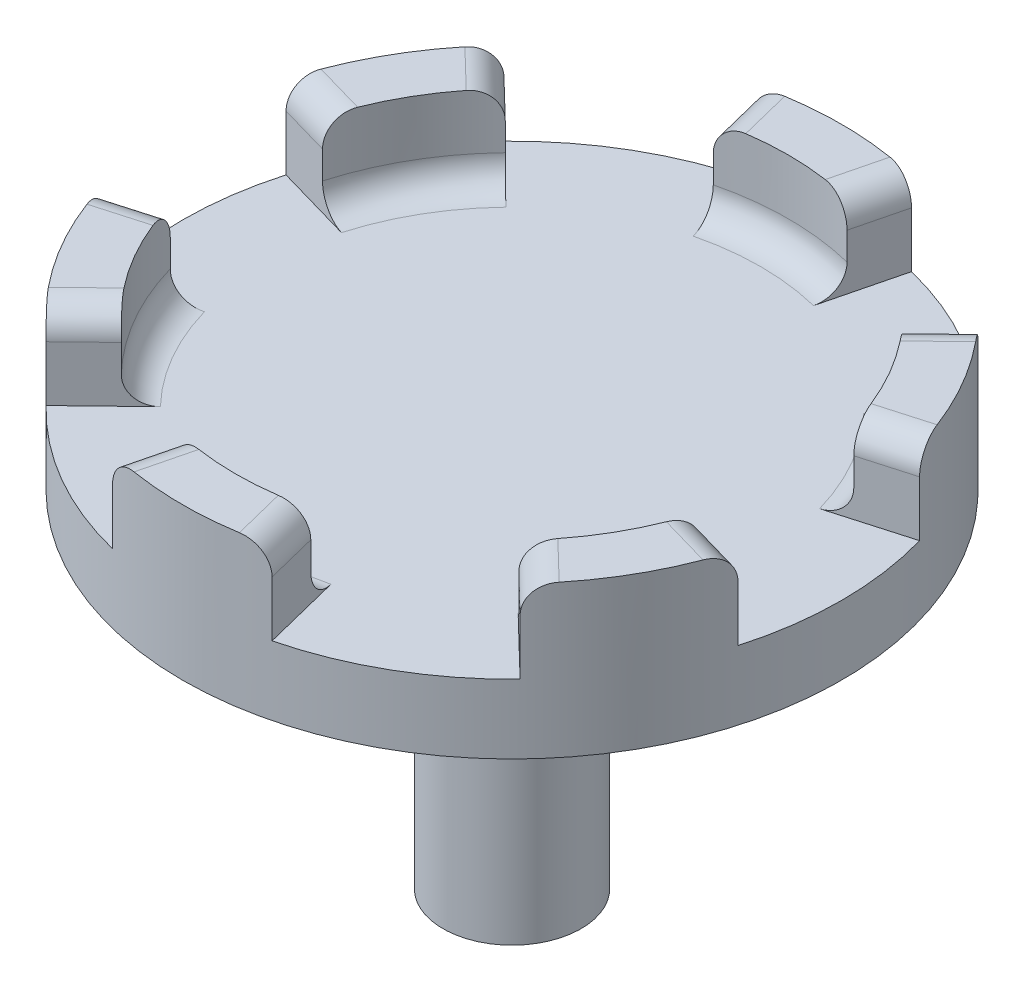
SolidWorks part; units mm, degrees
ref_plane "Front Plane" through (0, 0, 0) normal (0, 0, 1) x (1, 0, 0)
ref_plane "Top Plane" through (0, 0, 0) normal (0, 1, 0) x (1, 0, 0)
ref_plane "Right Plane" through (0, 0, 0) normal (1, 0, 0) x (0, 0, -1)
sketch "Sketch1" plane through (0, 0, 0) normal (0, 1, 0) x (1, 0, 0)
  circle A0 centre (0, 0) radius 30.2895
  dimension "D1" = 60.579
extrude "Boss-Extrude1" add sketch "Sketch1" along normal blind 6.35
sketch "Sketch2" plane through (0, 6.35, 0) normal (0, 1, 0) x (1, 0, 0)
  line L0 (-6.1482, -24.6447) -> (-7.3317, -29.3888)
  line L1 (-20.3643, -26.1375) -> (5.7009, -32.64) construction
  line L2 (-16.2324, -22.129) -> (3.936, -27.1604) construction
  line L3 (6.1482, -24.6447) -> (7.3317, -29.3888)
  line L4 (4.3414, -25.0954) -> (7.9549, -24.194) construction
  line L5 (8.1027, -29.1964) -> (6.5606, -29.5811) construction
  line L6 (-6.1482, -24.6447) -> (6.1482, -24.6447) construction
  line L7 (0, 0) -> (0, -49.2894) construction
  line L8 (-37.5524, 0) -> (37.5524, 0) construction
  line L9 (-24.417, -6.9979) -> (-29.1173, -8.345)
  line L10 (-18.2688, -17.6468) -> (-21.7856, -21.0438)
  line L11 (-18.2688, 17.6468) -> (-21.7856, 21.0438)
  line L12 (-24.417, 6.9979) -> (-29.1173, 8.345)
  line L13 (6.1482, 24.6447) -> (7.3317, 29.3888)
  line L14 (-6.1482, 24.6447) -> (-7.3317, 29.3888)
  line L15 (24.417, 6.9979) -> (29.1173, 8.345)
  line L16 (18.2688, 17.6468) -> (21.7856, 21.0438)
  line L17 (18.2688, -17.6468) -> (21.7856, -21.0438)
  line L18 (24.417, -6.9979) -> (29.1173, -8.345)
  line L19 (0, 0) -> (-6.1482, -24.6447) construction
  line L20 (0, 0) -> (-24.417, -6.9979) construction
  circle A0 centre (0, 0) radius 25.4 construction
  arc A1 (-18.2688, -17.6468) -> (-24.417, -6.9979) centre (0, 0) cw
  arc A2 (-21.7856, -21.0438) -> (-29.1173, -8.345) centre (0, 0) cw
  circle A3 centre (0, 0) radius 30.2895 construction
  arc A4 (6.1482, -24.6447) -> (-6.1482, -24.6447) centre (0, 0) cw
  arc A5 (7.3317, -29.3888) -> (-7.3317, -29.3888) centre (0, 0) cw
  arc A6 (-24.417, 6.9979) -> (-18.2688, 17.6468) centre (0, 0) cw
  arc A7 (-29.1173, 8.345) -> (-21.7856, 21.0438) centre (0, 0) cw
  arc A8 (-6.1482, 24.6447) -> (6.1482, 24.6447) centre (0, 0) cw
  arc A9 (-7.3317, 29.3888) -> (7.3317, 29.3888) centre (0, 0) cw
  arc A10 (18.2688, 17.6468) -> (24.417, 6.9979) centre (0, 0) cw
  arc A11 (21.7856, 21.0438) -> (29.1173, 8.345) centre (0, 0) cw
  arc A12 (24.417, -6.9979) -> (18.2688, -17.6468) centre (0, 0) cw
  arc A13 (29.1173, -8.345) -> (21.7856, -21.0438) centre (0, 0) cw
  point P10 (-7.3317, -29.3888)
  point P13 (-6.1482, -24.6447)
  point P18 (6.1482, -24.6447)
  point P20 (7.3317, -29.3888)
  point P23 (0, -24.6447)
  point P28 (0, 0)
  circle M16 centre (0, 0) radius 30.2895
  dimension "D1" = 50.8
  dimension "D2" = 6
  dimension "D3" = 60
extrude "Boss-Extrude2" add sketch "Sketch2" along normal blind 7.62 contours L3 A4 L0 M16 | L18 A12 L17 M16 | L16 A10 L15 M16 | L12 A6 L11 M16 | L10 A1 L9 M16 | A9 L13 A8 L14
fillet "Fillet1" radius 2.54 12 edges at (26.7671, 13.97, 7.6714) (26.7671, 13.97, -7.6714) (20.0272, 13.97, -19.3453) (6.7399, 13.97, -27.0167) (-6.7399, 13.97, -27.0167) (-20.0272, 13.97, -19.3453) (-26.7671, 13.97, -7.6714) (-26.7671, 13.97, 7.6714) (-20.0272, 13.97, 19.3453) (-6.7399, 13.97, 27.0167) (20.0272, 13.97, 19.3453) (6.7399, 13.97, 27.0167)
sketch "Sketch3" plane through (0, 0, 0) normal (0, -1, 0) x (1, 0, 0)
  circle A0 centre (0, 0) radius 8.89
  dimension "D1" = 17.78
extrude "Boss-Extrude3" add sketch "Sketch3" along normal blind 6.35
fillet "Fillet2" radius 2.54 6 edges at (-21.997, 6.35, 12.7) (-21.997, 6.35, -12.7) (0, 6.35, -25.4) (21.997, 6.35, -12.7) (0, 6.35, 25.4) (21.997, 6.35, 12.7)
sketch "Sketch4" plane through (0, -6.35, 0) normal (0, -1, 0) x (1, 0, 0)
  circle A0 centre (0, 0) radius 6.35
  dimension "D1" = 12.7
extrude "Boss-Extrude4" add sketch "Sketch4" along normal blind 25.4
